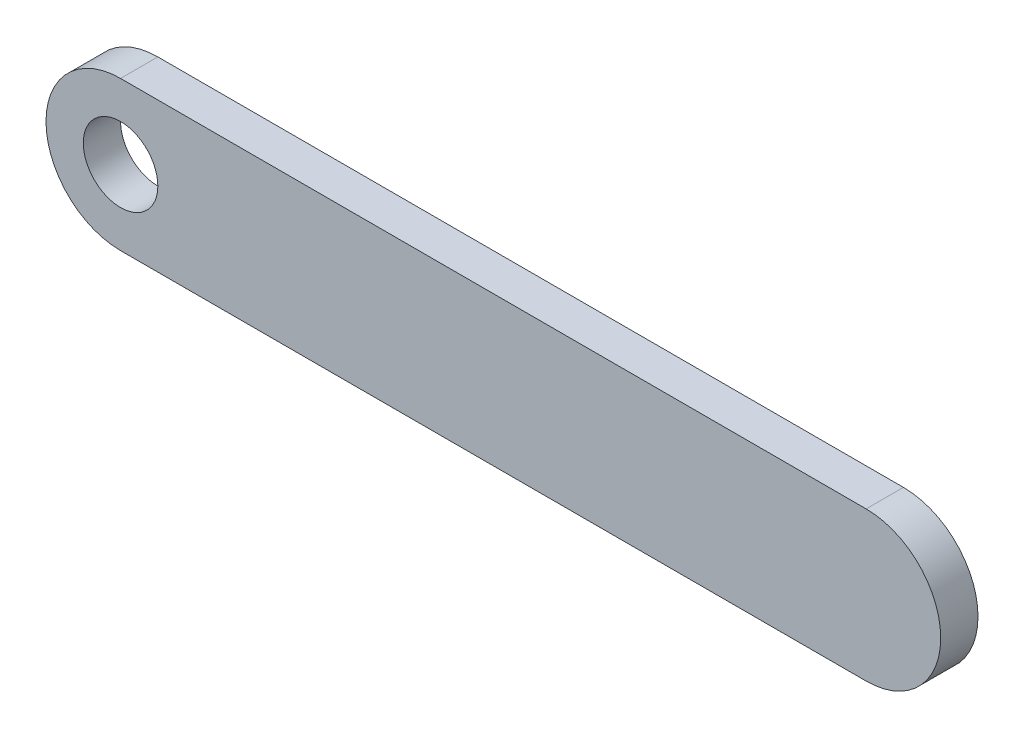
SolidWorks part; units mm, degrees
ref_plane "Alzado" through (0, 0, 0) normal (0, 0, 1) x (1, 0, 0)
ref_plane "Planta" through (0, 0, 0) normal (0, 1, 0) x (1, 0, 0)
ref_plane "Vista lateral" through (0, 0, 0) normal (1, 0, 0) x (0, 0, -1)
sketch "Croquis1" plane through (0, 0, 0) normal (0, 0, 1) x (1, 0, 0)
  line L0 (0, 0) -> (100, 0) construction
  line L1 (0, 10) -> (100, 10)
  line L2 (0, -10) -> (100, -10)
  circle A0 centre (0, 0) radius 5
  arc A1 (0, 10) -> (0, -10) centre (0, 0) ccw
  arc A2 (100, -10) -> (100, 10) centre (100, 0) ccw
  point P3 (50, 0)
  dimension "D1" = 10
  dimension "D2" = 10
  dimension "D3" = 100
extrude "Saliente-Extruir1" add sketch "Croquis1" along normal blind 5
